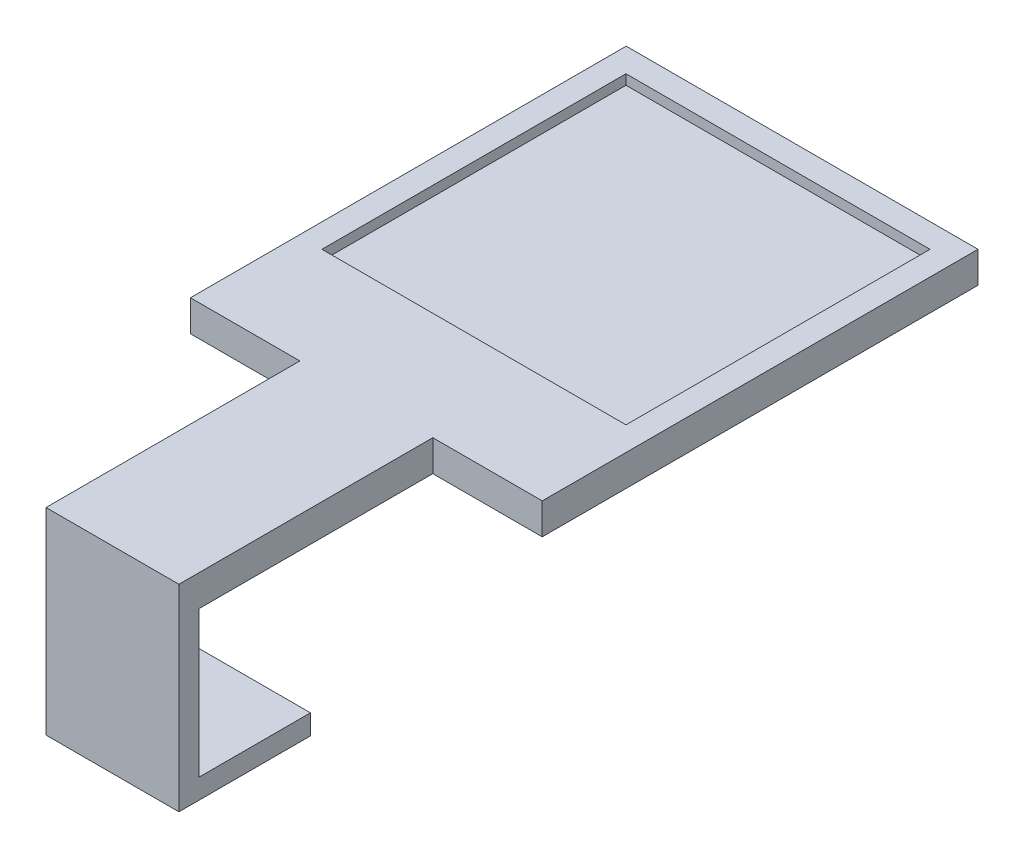
SolidWorks part; units mm, degrees
ref_plane "前视基准面" through (0, 0, 0) normal (0, 0, 1) x (1, 0, 0)
ref_plane "上视基准面" through (0, 0, 0) normal (0, 1, 0) x (1, 0, 0)
ref_plane "右视基准面" through (0, 0, 0) normal (1, 0, 0) x (0, 0, -1)
sketch "草图1" plane through (0, 0, 0) normal (0, 1, 0) x (1, 0, 0)
  line L1 (-7.8276, 6.7094) -> (9.7724, 6.7094)
  line L2 (-7.8276, 6.7094) -> (-7.8276, -15.0906)
  line L3 (-7.8276, -15.0906) -> (9.7724, -15.0906)
  line L4 (9.7724, 6.7094) -> (9.7724, -15.0906)
  dimension "D1" = 17.6
  dimension "D2" = 21.8
extrude "凸台-拉伸1" add sketch "草图1" along normal blind 1.56
sketch "草图2" plane through (0, 1.56, 0) normal (0, 1, 0) x (1, 0, 0)
  line L0 (9.7724, -15.0906) -> (9.7724, 6.7094) construction
  line L5 (-6.6376, 5.5094) -> (8.5724, 5.5094)
  line L6 (-6.6376, 5.5094) -> (-6.6376, -9.7006)
  line L7 (-6.6376, -9.7006) -> (8.5724, -9.7006)
  line L8 (8.5724, 5.5094) -> (8.5724, -9.7006)
  line L9 (9.7724, 6.7094) -> (-7.8276, 6.7094) construction
  dimension "D1" = 15.21
  dimension "D2" = 15.21
  dimension "D3" = 1.2
  dimension "D4" = 1.2
extrude "切除-拉伸1" cut sketch "草图2" against normal blind 0.5
sketch "草图3" plane through (0, 0, 15.0906) normal (0, 0, 1) x (1, 0, 0)
  line L0 (-7.8276, 1.56) -> (9.7724, 1.56) construction
  line L1 (-2.3526, 1.56) -> (4.2974, 1.56)
  line L2 (-2.3526, 1.56) -> (-2.3526, 0)
  line L3 (-2.3526, 0) -> (4.2974, 0)
  line L4 (4.2974, 1.56) -> (4.2974, 0)
  line L5 (-7.8276, 0) -> (9.7724, 0) construction
  point P8 (0.9724, 1.56)
  dimension "D1" = 6.65
extrude "凸台-拉伸2" add sketch "草图3" along normal blind 25.58
sketch "草图4" plane through (0, 0, 0) normal (0, 1, 0) x (1, 0, 0)
  line L1 (-2.3526, -26.7906) -> (4.2974, -26.7906)
  line L2 (-2.3526, -26.7906) -> (-2.3526, -27.7906)
  line L3 (-2.3526, -27.7906) -> (4.2974, -27.7906)
  line L4 (4.2974, -26.7906) -> (4.2974, -27.7906)
  line L6 (4.2974, -40.6706) -> (-2.3526, -40.6706) construction
  dimension "D1" = 13.88
  dimension "D2" = 1
extrude "凸台-拉伸3" add sketch "草图4" against normal blind 12.88
sketch "草图5" plane through (0, 0, 26.7906) normal (0, 0, -1) x (-1, 0, 0)
  line L0 (-4.2974, -12.88) -> (-4.2974, 0) construction
  line L1 (-4.2974, -7.3) -> (2.3526, -7.3)
  line L2 (-4.2974, -7.3) -> (-4.2974, -8.3)
  line L3 (-4.2974, -8.3) -> (2.3526, -8.3)
  line L4 (2.3526, -7.3) -> (2.3526, -8.3)
  line L5 (2.3526, -12.88) -> (2.3526, 0) construction
  line L6 (-4.2974, 0) -> (2.3526, 0) construction
  line L7 (-4.2974, -12.88) -> (2.3526, -12.88) construction
  dimension "D1" = 7.3
  dimension "D2" = 1
  dimension "D3" = 4.58
extrude "凸台-拉伸4" add sketch "草图5" along normal blind 5.58
sketch "草图6" plane through (0, 0, 0) normal (0, -1, 0) x (1, 0, 0)
  line L1 (-2.3526, 40.6706) -> (4.2974, 40.6706)
  line L2 (-2.3526, 40.6706) -> (-2.3526, 27.7906)
  line L3 (-2.3526, 27.7906) -> (4.2974, 27.7906)
  line L4 (4.2974, 40.6706) -> (4.2974, 27.7906)
extrude "切除-拉伸2" cut sketch "草图6" against normal up to next
sketch "草图7" plane through (0, 0, 26.7906) normal (0, 0, -1) x (-1, 0, 0)
  line L0 (-4.2974, -12.88) -> (-4.2974, -8.3) construction
  line L1 (-4.2974, -8.3) -> (2.3526, -8.3)
  line L2 (-4.2974, -8.3) -> (-4.2974, -12.88)
  line L3 (-4.2974, -12.88) -> (2.3526, -12.88)
  line L4 (2.3526, -8.3) -> (2.3526, -12.88)
  line L5 (-4.2974, -8.3) -> (2.3526, -8.3) construction
extrude "切除-拉伸3" cut sketch "草图7" against normal up to next
